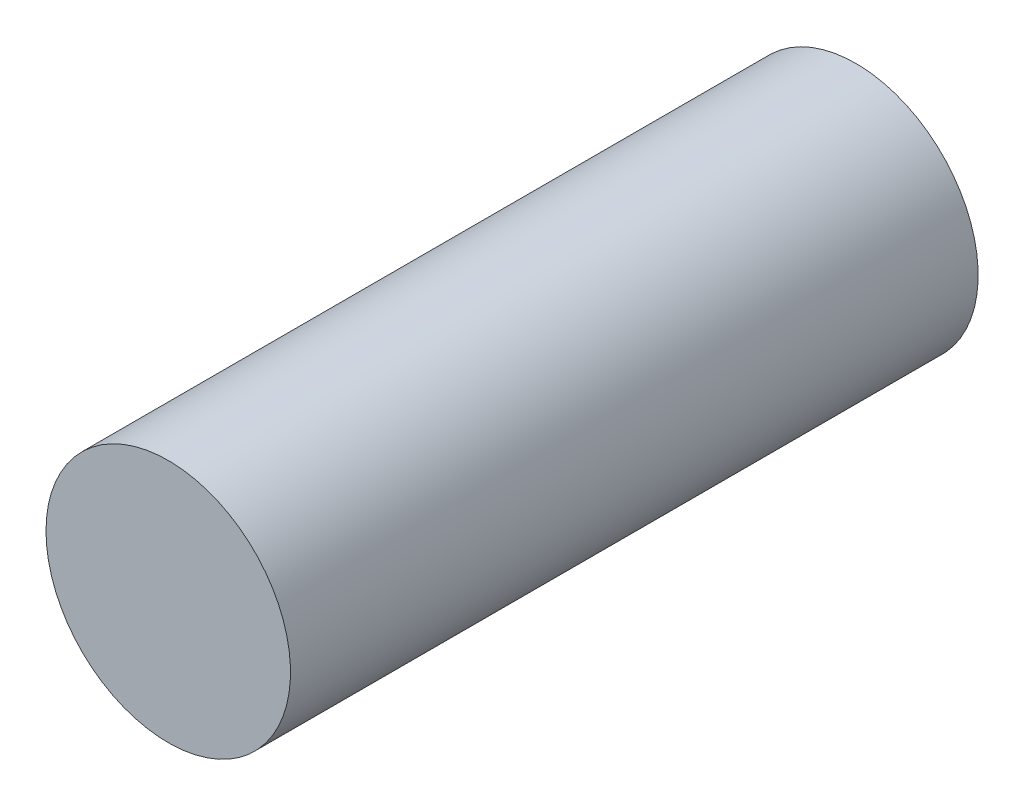
SolidWorks part; units mm, degrees
ref_plane "Front Plane" through (0, 0, 0) normal (0, 0, 1) x (1, 0, 0)
ref_plane "Top Plane" through (0, 0, 0) normal (0, 1, 0) x (1, 0, 0)
ref_plane "Right Plane" through (0, 0, 0) normal (1, 0, 0) x (0, 0, -1)
sketch "Sketch1" plane through (0, 0, 0) normal (0, 0, 1) x (1, 0, 0)
  circle A0 centre (0, 0) radius 8
  dimension "D1" = 16
extrude "Boss-Extrude1" add sketch "Sketch1" along normal blind 45
